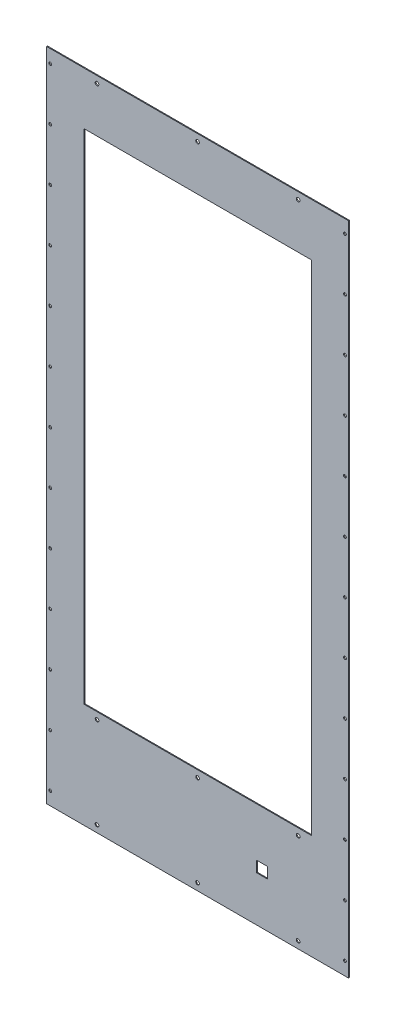
SolidWorks part; units mm, degrees
ref_plane "Front Plane" through (0, 0, 0) normal (0, 0, 1) x (1, 0, 0)
ref_plane "Top Plane" through (0, 0, 0) normal (0, 1, 0) x (1, 0, 0)
ref_plane "Right Plane" through (0, 0, 0) normal (1, 0, 0) x (0, 0, -1)
sketch "Sketch1" plane through (0, 0, 0) normal (0, 0, 1) x (1, 0, 0)
  line L0 (-673.5642, -82.6035) -> (-328.5642, -82.6035)
  line L1 (-328.5642, -82.6035) -> (-328.5642, -832.6035)
  line L4 (-673.5642, -82.6035) -> (-673.5642, -832.6035)
  line L5 (-673.5642, -832.6035) -> (-328.5642, -832.6035)
  line L6 (-371.0198, -712.6035) -> (-631.0198, -712.6035)
  line L7 (-631.0198, -712.6035) -> (-631.0198, -142.6035)
  line L8 (-631.0198, -142.6035) -> (-371.0198, -142.6035)
  line L9 (-371.0198, -142.6035) -> (-371.0198, -712.6035)
  line L11 (-433.4198, -768.4035) -> (-420.9198, -768.4035)
  line L13 (-420.9198, -768.4035) -> (-420.9198, -780.9035)
  line L32 (-420.9198, -780.9035) -> (-433.4198, -780.9035)
  line L42 (-433.4198, -780.9035) -> (-433.4198, -768.4035)
  circle A32 centre (-501.0642, -90.6035) radius 2.1
  circle A33 centre (-616.0642, -90.6035) radius 2.1
  circle A34 centre (-386.0642, -90.6035) radius 2.1
  circle A35 centre (-616.0198, -720.6035) radius 2.1
  circle A36 centre (-501.0198, -720.6035) radius 2.1
  circle A37 centre (-386.0198, -720.6035) radius 2.1
  circle A38 centre (-386.0642, -824.6035) radius 2.1
  circle A39 centre (-501.0642, -824.6035) radius 2.1
  circle A40 centre (-616.0642, -824.6035) radius 2.1
  point P86 (-501.0198, -821.9735)
extrude "Boss-Extrude1" add sketch "Sketch1" along normal blind 1
sketch "Sketch2" plane through (0, 0, 1) normal (0, 0, 1) x (1, 0, 0)
  line L0 (-673.5642, -82.6035) -> (-665.7042, -82.6035)
  line L1 (-673.5642, -82.6035) -> (-328.5642, -82.6035) construction
  line L5 (-665.7042, -97.6035) -> (-669.6342, -97.6035)
  circle A0 centre (-669.6342, -97.6035) radius 1.6
  circle A1 centre (-669.6342, -817.6035) radius 1.6
  circle A2 centre (-669.6342, -757.6035) radius 1.6
  circle A3 centre (-669.6342, -697.6035) radius 1.6
  circle A4 centre (-669.6342, -637.6035) radius 1.6
  circle A5 centre (-669.6342, -577.6035) radius 1.6
  circle A6 centre (-669.6342, -517.6035) radius 1.6
  circle A7 centre (-669.6342, -457.6035) radius 1.6
  circle A8 centre (-669.6342, -397.6035) radius 1.6
  circle A9 centre (-669.6342, -337.6035) radius 1.6
  circle A10 centre (-669.6342, -277.6035) radius 1.6
  circle A11 centre (-669.6342, -217.6035) radius 1.6
  circle A12 centre (-669.6342, -157.6035) radius 1.6
extrude "Cut-Extrude1" cut sketch "Sketch2" against normal blind 1 contours A1 | A2 | A3 | A4 | A5 | A6 | A7 | A8 | A9 | A10 | A11 | A12 | A0
sketch "Sketch3" plane through (0, 0, 1) normal (0, 0, 1) x (1, 0, 0)
  circle A0 centre (-332.5142, -97.6035) radius 1.6
  circle A1 centre (-332.5142, -817.6035) radius 1.6
  circle A2 centre (-332.5142, -757.6035) radius 1.6
  circle A3 centre (-332.5142, -697.6035) radius 1.6
  circle A4 centre (-332.5142, -637.6035) radius 1.6
  circle A5 centre (-332.5142, -577.6035) radius 1.6
  circle A6 centre (-332.5142, -517.6035) radius 1.6
  circle A7 centre (-332.5142, -457.6035) radius 1.6
  circle A8 centre (-332.5142, -397.6035) radius 1.6
  circle A9 centre (-332.5142, -337.6035) radius 1.6
  circle A10 centre (-332.5142, -277.6035) radius 1.6
  circle A11 centre (-332.5142, -217.6035) radius 1.6
  circle A12 centre (-332.5142, -157.6035) radius 1.6
extrude "Cut-Extrude2" cut sketch "Sketch3" against normal blind 1
